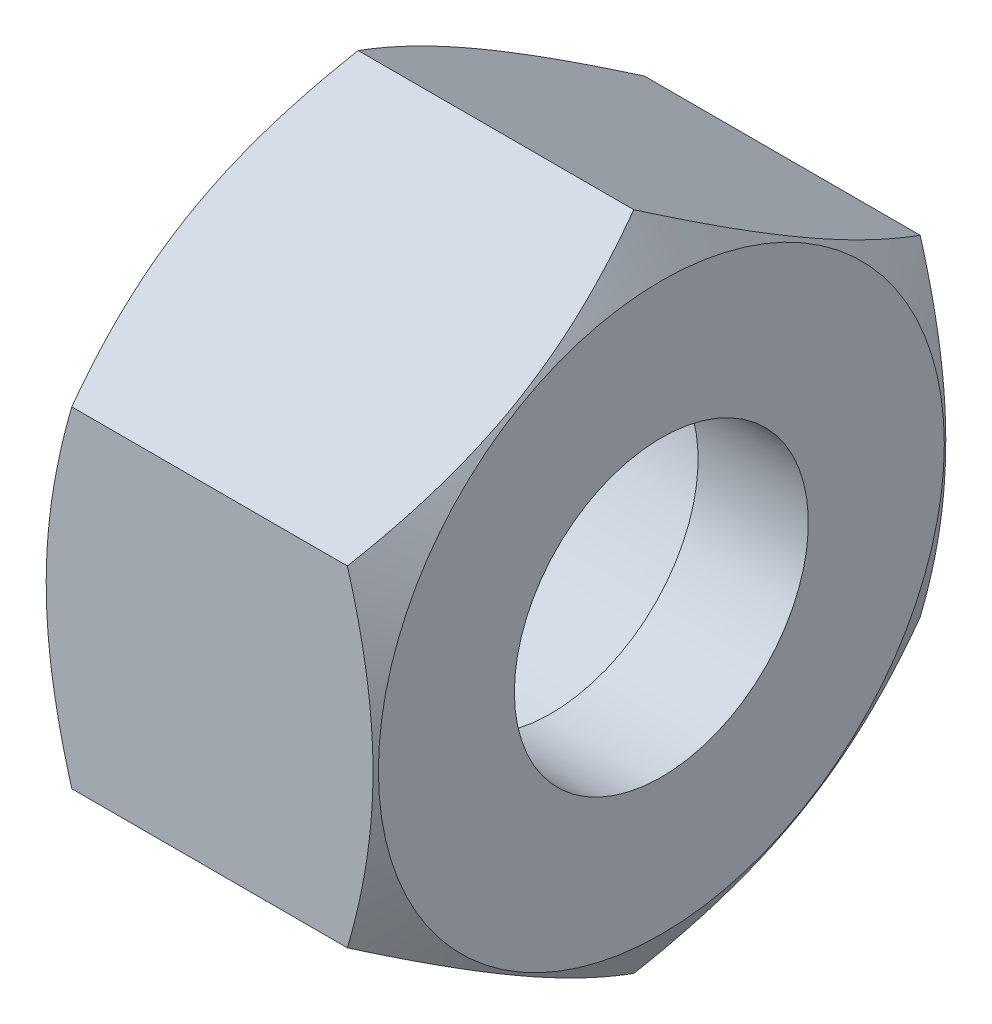
SolidWorks part; units mm, degrees
ref_plane "Спереди" through (0, 0, 0) normal (0, 0, 1) x (1, 0, 0)
ref_plane "Сверху" through (0, 0, 0) normal (0, 1, 0) x (1, 0, 0)
ref_plane "Справа" through (0, 0, 0) normal (1, 0, 0) x (0, 0, -1)
sketch "Эскиз1" plane through (0, 0, 0) normal (0, 0, 1) x (1, 0, 0)
  line L0 (0, 0) -> (14.825, 0) construction
  line L1 (0, 0) -> (0, 12) construction
  line L3 (18, 12) -> (18, 15.4019)
  line L4 (18, 15.4019) -> (16.5, 18)
  line L5 (16.5, 18) -> (1.5, 18)
  line L6 (1.5, 18) -> (0, 15.4019)
  line L7 (0, 15.4019) -> (0, 12)
  line L8 (18, 12) -> (18, 8)
  line L14 (18, 8) -> (12, 8)
  line L15 (12, 8) -> (12, 13)
  line L17 (0, 12) -> (10, 12)
  line L18 (10, 12) -> (10, 13)
  line L19 (10, 13) -> (12, 13)
  point P12 (11, 13)
  dimension "D1" = 2
  dimension "D2" = 18
  dimension "D3" = 60
  dimension "D4" = 60
  dimension "D5" = 1.5
  dimension "D6" = 1.5
  dimension "D7" = 18
  dimension "D8" = 12
  dimension "D9" = 16
  dimension "D10" = 24
  dimension "D11" = 26
revolve "Повернуть1" add sketch "Эскиз1" angle 360 about L0
sketch "Эскиз2" plane through (18, 0, 0) normal (1, 0, 0) x (0, 0, -1)
  line L1 (0, 18) -> (-15.5885, 9)
  line L2 (-15.5885, 9) -> (-15.5885, -9)
  line L3 (-15.5885, -9) -> (0, -18)
  line L4 (0, -18) -> (15.5885, -9)
  line L5 (15.5885, -9) -> (15.5885, 9)
  line L6 (15.5885, 9) -> (0, 18)
  circle A0 centre (0, 0) radius 15.5885 construction
extrude "Вырез-Вытянуть1" cut sketch "Эскиз2" against normal blind 30 flip side to cut
